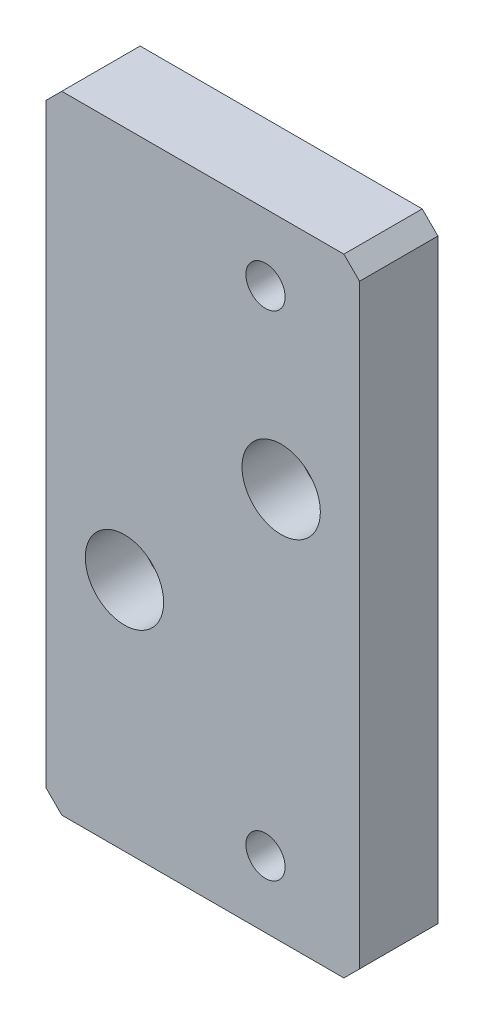
SolidWorks part; units mm, degrees
material "3.1325 (EN-AW 2017A)"
ref_plane "Plan de face" through (0, 0, 0) normal (0, 0, 1) x (1, 0, 0)
ref_plane "Plan de dessus" through (0, 0, 0) normal (0, 1, 0) x (1, 0, 0)
ref_plane "Plan de droite" through (0, 0, 0) normal (1, 0, 0) x (0, 0, -1)
sketch "Esquisse1" plane through (0, 0, 0) normal (0, 0, 1) x (1, 0, 0)
  line L1 (20, 40) -> (-20, 40)
  line L2 (20, 40) -> (20, -40)
  line L3 (20, -40) -> (-20, -40)
  line L4 (-20, 40) -> (-20, -40)
  line L5 (20, 40) -> (-20, -40) construction
  line L6 (20, -40) -> (-20, 40) construction
  point P0 (0, 0)
  dimension "D1" = 40
  dimension "D2" = 80
extrude "Boss.-Extru.1" add sketch "Esquisse1" along normal blind 10
chamfer "Chanfrein1" distance 2 angle 45 4 edges at (-20, -40, 5) (20, -40, 5) (-20, 40, 5) (20, 40, 5)
hole_wizard "Trou taraudé M61" positions "Esquisse5" profile "Esquisse4" tap size "M6" standard "ISO" end condition through all
sketch "Esquisse5" plane through (0, 0, 10) normal (0, 0, 1) x (1, 0, 0)
  line L0 (20, -38) -> (20, 38) construction
  line L1 (18, 40) -> (-18, 40) construction
  point P0 (8, 31.5)
  point P3 (8, -31.5)
  dimension "D1" = 12
  dimension "D2" = 8.5
  dimension "D3" = 63
sketch "Esquisse4" plane through (8, 31.5, 10) normal (1, 0, 0) x (0, -1, 0)
  line L0 (0, 0) -> (0, 10)
  line L1 (0, 10) -> (2.5, 10)
  line L2 (2.5, 10) -> (2.5, 0)
  line L5 (2.5, 0) -> (0, 0)
  line L11 (0, -6.35) -> (0, 107.95) construction
  dimension "Diamètre du trou pour taraudage jusqu'au prochain" = 5
  dimension "Profondeur du trou pour taraudage jusqu'au prochain" = 10
cosmetic thread "Filetage de perçage1" parameters "D2"=6
cosmetic thread "Filetage de perçage2" parameters "D2"=6
hole_wizard "Chambrage pour vis à tête hexagonale M51" positions "Esquisse7" profile "Esquisse6" counterbore size "M5" standard "ISO" end condition through all
sketch "Esquisse7" plane through (0, 0, 10) normal (0, 0, 1) x (1, 0, 0)
  point P0 (10, 10)
  point P3 (-10, -10)
sketch "Esquisse6" plane through (10, 10, 10) normal (1, 0, 0) x (0, -1, 0)
  line L0 (0, 0) -> (0, 10)
  line L1 (0, 10) -> (2.75, 10)
  line L3 (2.75, 10) -> (2.75, 7)
  line L4 (2.75, 7) -> (5, 7)
  line L5 (5, 7) -> (5, 0)
  line L7 (5, 0) -> (0, 0)
  line L11 (0, -6.35) -> (0, 107.95) construction
  dimension "Diamètre du perçage jusqu'au prochain" = 5.5
  dimension "Profondeur du perçage jusqu'au prochain" = 10
  dimension "Diamètre du chambrage" = 10
  dimension "Profondeur du chambrage" = 7
